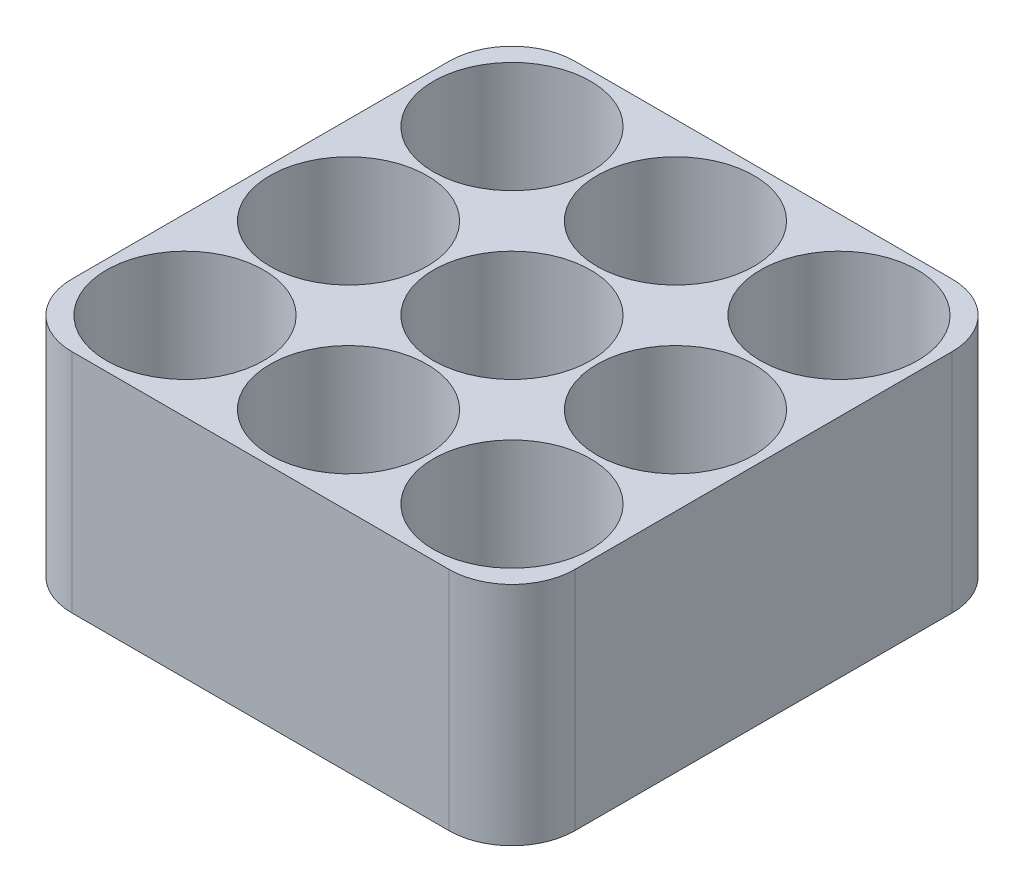
SolidWorks part; units mm, degrees
ref_plane "Front Plane" through (0, 0, 0) normal (0, 0, 1) x (1, 0, 0)
ref_plane "Top Plane" through (0, 0, 0) normal (0, 1, 0) x (1, 0, 0)
ref_plane "Right Plane" through (0, 0, 0) normal (1, 0, 0) x (0, 0, -1)
sketch "Sketch2" plane through (0, 0, 0) normal (0, 1, 0) x (1, 0, 0)
  line L0 (26, 38.5) -> (26, 13.5) construction
  line L1 (26, 13.5) -> (38.5, 26) construction
  line L2 (38.5, 26) -> (13.5, 26) construction
  line L4 (-14, -14) -> (66, -14)
  line L5 (-14, -14) -> (-14, 66)
  line L6 (-14, 66) -> (66, 66)
  line L7 (66, -14) -> (66, 66)
  line L8 (-14, -14) -> (66, 66) construction
  line L9 (-14, 66) -> (66, -14) construction
  circle A0 centre (0, 0) radius 12.5
  circle A1 centre (26, 0) radius 12.5
  circle A2 centre (52, 0) radius 12.5
  circle A3 centre (26, 26) radius 12.5
  circle A4 centre (52, 26) radius 12.5
  circle A5 centre (26, 52) radius 12.5
  circle A6 centre (52, 52) radius 12.5
  circle A7 centre (0, 26) radius 12.5
  circle A8 centre (0, 52) radius 12.5
  dimension "D1" = 25
  dimension "D4" = 80
  dimension "D5" = 80
  dimension "D2" = 3
  dimension "D3" = 3
extrude "Boss-Extrude2" add sketch "Sketch2" along normal blind 35
sketch "Sketch3" plane through (0, 0, 0) normal (0, -1, 0) x (1, 0, 0)
  line L0 (-14, 14) -> (66, 14) construction
  line L1 (66, 14) -> (-14, 14)
  line L2 (66, 14) -> (66, -66)
  line L3 (66, -66) -> (-14, -66)
  line L4 (-14, 14) -> (-14, -66)
  line L5 (66, 14) -> (66, -66) construction
extrude "Boss-Extrude3" add sketch "Sketch3" along normal blind 1
fillet "Fillet1" radius 10 4 edges at (66, 17, 14) (-14, 17, 14) (-14, 17, -66) (66, 17, -66)
